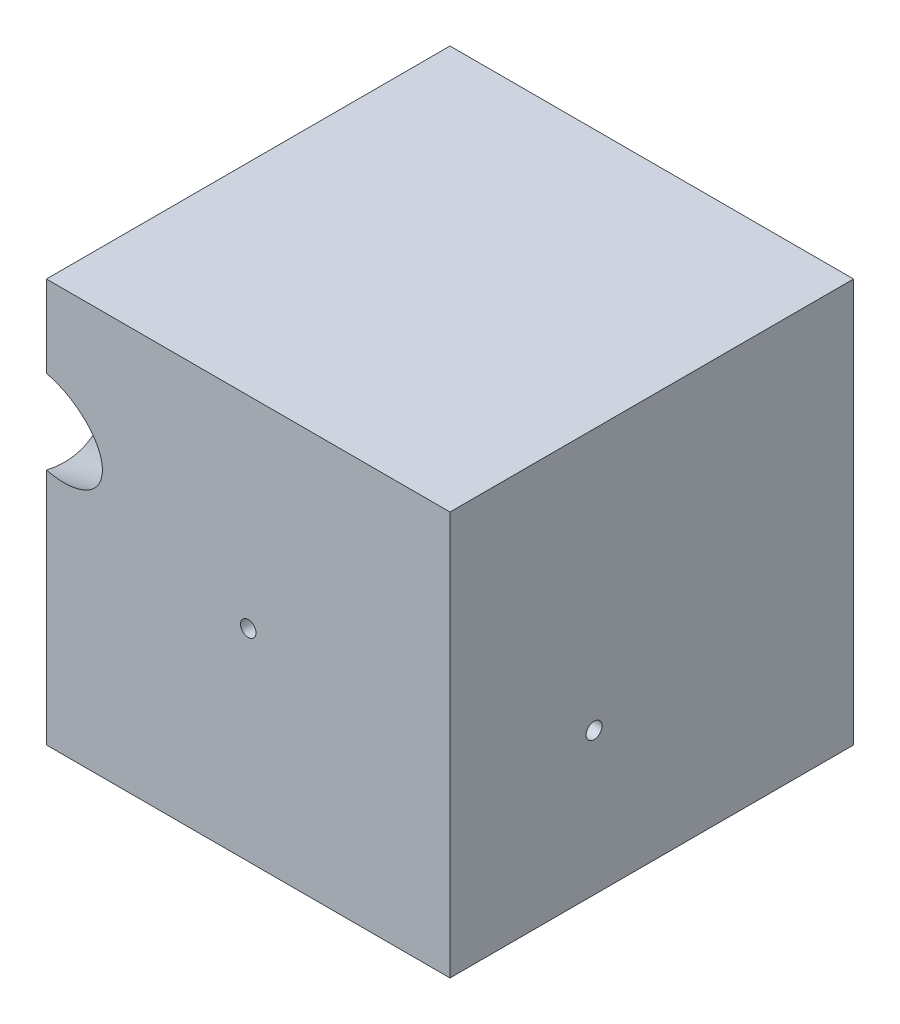
SolidWorks part; units mm, degrees
material "ABS"
ref_plane "Front Plane" through (0, 0, 0) normal (0, 0, 1) x (1, 0, 0)
ref_plane "Top Plane" through (0, 0, 0) normal (0, 1, 0) x (1, 0, 0)
ref_plane "Right Plane" through (0, 0, 0) normal (1, 0, 0) x (0, 0, -1)
sketch "Square" plane through (0, 0, 0) normal (0, 0, 1) x (1, 0, 0)
  line L1 (-26, -26) -> (26, -26)
  line L2 (-26, -26) -> (-26, 26)
  line L3 (-26, 26) -> (26, 26)
  line L4 (26, -26) -> (26, 26)
  line L5 (-26, -26) -> (26, 26) construction
  line L6 (-26, 26) -> (26, -26) construction
  point P0 (0, 0)
  dimension "D1" = 52
extrude "Cube-Extrusion" add sketch "Square" along normal blind 52
ref_plane "StickPlane" through (-28.8889, 14.4444, 28.8889) normal (0.6667, -0.3333, -0.6667) x (-0.7454, -0.2981, -0.5963)
sketch "Stick-Hole" plane through (-28.8889, 14.4444, 28.8889) normal (0.6667, -0.3333, -0.6667) x (-0.7454, -0.2981, -0.5963)
  line L0 (-19.3793, 0) -> (-3.8759, -46.5102) construction
  circle A0 centre (-14.6358, -14.2302) radius 5.1
  dimension "D2" = 10.2
  dimension "D1" = 15
extrude "Stick-Cut" cut sketch "Stick-Hole" against normal through all from offset 15
sketch "Sketch12" plane through (0, 0, 52) normal (0, 0, 1) x (1, 0, 0)
  circle A0 centre (0, 0) radius 1
  dimension "D1" = 2
extrude "Cut-Extrude8" cut sketch "Sketch12" against normal blind 12
sketch "Sketch13" plane through (0, 0, 0) normal (0, 0, -1) x (-1, 0, 0)
  circle A0 centre (0, 0) radius 1
  dimension "D1" = 2
extrude "Cut-Extrude9" cut sketch "Sketch13" against normal blind 12
sketch "Sketch14" plane through (-26, 0, 0) normal (-1, 0, 0) x (0, 0, 1)
  line L0 (0, 26) -> (0, -26) construction
  line L1 (52, 26) -> (0, 26) construction
  line L2 (52, -26) -> (0, -26) construction
  circle A0 centre (10.5144, 15.4825) radius 1
  circle A1 centre (20.4493, -13.8146) radius 1
  dimension "D1" = 2
  dimension "D2" = 10.5144
  dimension "D3" = 10.5175
  dimension "D4" = 20.4493
  dimension "D5" = 12.1854
extrude "Cut-Extrude10" cut sketch "Sketch14" against normal blind 12
sketch "Sketch15" plane through (26, 0, 0) normal (1, 0, 0) x (0, 0, -1)
  circle A0 centre (-33.4399, -7.6506) radius 1.0307
extrude "Cut-Extrude11" cut sketch "Sketch15" against normal blind 12
sketch "Sketch16" plane through (0, -26, 0) normal (0, -1, 0) x (1, 0, 0)
  line L0 (-26, 52) -> (-26, 0) construction
  line L1 (-26, 0) -> (26, 0) construction
  circle A0 centre (-9, 44.28) radius 1
  dimension "D3" = 2
  dimension "D1" = 17
  dimension "D2" = 44.28
extrude "Cut-Extrude12" cut sketch "Sketch16" against normal blind 12
